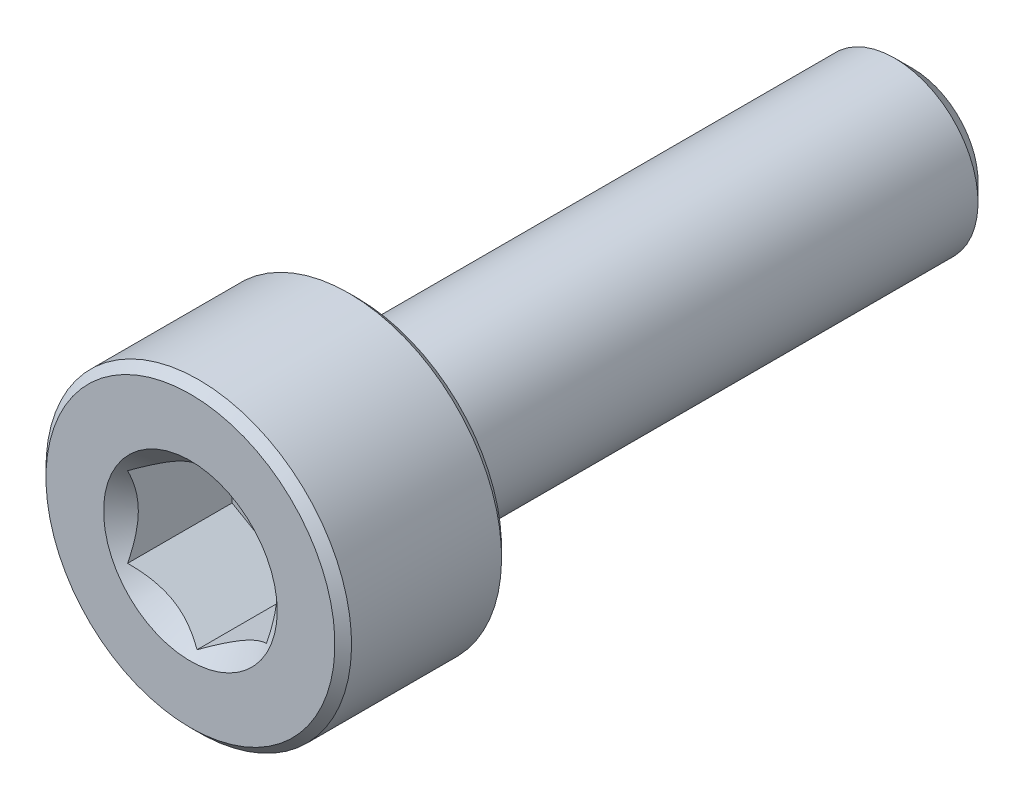
SolidWorks part; units mm, degrees
ref_plane "Front Plane" through (0, 0, 0) normal (0, 0, 1) x (1, 0, 0)
ref_plane "Top Plane" through (0, 0, 0) normal (0, 1, 0) x (1, 0, 0)
ref_plane "Right Plane" through (0, 0, 0) normal (1, 0, 0) x (0, 0, -1)
sketch "Sketch1" plane through (0, 0, 0) normal (1, 0, 0) x (0, 0, -1)
  line L0 (-6.5, 0) -> (6.5, 0) construction
  line L1 (6.5, 0) -> (6.5, 1.1752) construction
  line L2 (6.5, 1.1752) -> (6.1752, 1.5) construction
  line L3 (6.1752, 1.5) -> (6.125, 1.5) construction
  line L4 (6.125, 1.5) -> (-3.5, 1.5) construction
  line L5 (-3.5, 1.5) -> (-3.5, 2.75) construction
  line L6 (-3.5, 2.75) -> (-6.5, 2.75) construction
  line L7 (-6.5, 2.75) -> (-6.5, 0) construction
  line L8 (6.5, 1.1752) -> (6.5, 1.5) construction
  line L9 (6.4688, 1.5541) -> (6.7188, 1.1211) construction
  line L10 (6.7188, 1.1211) -> (6.9688, 1.5541) construction
  line L11 (6.9688, 1.5541) -> (6.4688, 1.5541) construction
  line L12 (6.7188, 1.5541) -> (6.7188, 1.5) construction
  line L13 (6.7188, 1.1211) -> (6.7188, 1.1752) construction
  line L14 (6.6875, 1.1752) -> (6.75, 1.1752) construction
  line L15 (6.5, 1.5) -> (6.9375, 1.5) construction
  line L16 (6.4844, 1.5271) -> (6.9531, 1.5271) construction
  line L17 (6.5, 0) -> (6.5, -1.5) construction
  line L18 (-3.65, 2.75) -> (-3.5, 2.6) construction
  line L19 (-6.35, 2.75) -> (-6.5, 2.6) construction
  line L20 (-3.5, 1.5) -> (-3.5, 0) construction
  line L21 (-3.5, 0.75) -> (-0.1667, 0.75) construction
  line L22 (-0.1667, 0.75) -> (3.1667, 0.75) construction
  line L23 (3.1667, 0.75) -> (6.5, 0.75) construction
  line L24 (-0.1667, 0.75) -> (-0.1667, 1.5) construction
  line L25 (-0.1667, 1.5) -> (-0.1667, 2.75) construction
  line L26 (3.1667, 0.75) -> (3.1667, 2.75) construction
  point P0 (-6.5, 1.25)
  point P3 (5.25, 1.5)
  point P4 (0, 0)
  point P18 (3.1667, 1.5)
  point P22 (6.7188, 1.1752)
  point P24 (6.125, 1.5)
  point P25 (6.7188, 1.5)
  point P28 (6.7188, 1.5271)
  point P29 (5.25, -1.5)
  point P30 (-0.1667, 1.5)
  point P31 (-5, 2.75)
  point P37 (-4.025, 2.75)
  point P38 (-6.275, 2.75)
  point P45 (-0.1667, 0.75)
  point P46 (3.1667, 0.75)
  dimension "D2" = 0.0625
  dimension "D7" = 0.15
  dimension "D8" = 0.15
  dimension "D9" = 0.15
  dimension "D10" = 0.075
  dimension "D11" = 0.375
  dimension "Drive Size" = 2.5
  dimension "Head Diameter" = 5.5
  dimension "Head Height" = 3
  dimension "Thread Pitch" = 0.5
  dimension "Thread Size" = 3
  dimension "Length" = 10
  dimension "D12" = 0.375
  dimension "D4" = 1.25
  dimension "D3" = 45
sketch "Sketch2" plane through (0, 0, 0) normal (1, 0, 0) x (0, 0, -1)
  line L0 (-6.5, 0) -> (-6.5, 2.6)
  line L1 (-6.35, 2.75) -> (-3.65, 2.75)
  line L2 (-3.5, 2.6) -> (-3.5, 1.65)
  line L4 (6.1752, 1.5) -> (6.5, 1.1752)
  line L5 (6.5, 1.1752) -> (6.5, 0)
  line L6 (-3.5, 2.75) -> (-6.5, 2.75) construction
  line L7 (6.5, 0) -> (-6.5, 0)
  line L8 (-6.35, 2.75) -> (-6.5, 2.6) construction
  line L10 (-6.35, 2.75) -> (-6.5, 2.6)
  line L14 (-3.65, 2.75) -> (-3.5, 2.6) construction
  line L16 (-3.65, 2.75) -> (-3.5, 2.6)
  line L17 (-3.5, 1.5) -> (-3.5, 2.75) construction
  line L19 (-3.35, 1.5) -> (6.1752, 1.5)
  line L20 (6.125, 1.5) -> (-3.5, 1.5) construction
  arc A1 (-3.5, 1.65) -> (-3.35, 1.5) centre (-3.35, 1.65) ccw
  dimension "D3" = 0.15
revolve "Revolve1" add sketch "Sketch2" angle 360 about L7
sketch "Sketch3" plane through (0, 0, 6.5) normal (0, 0, 1) x (1, 0, 0)
  line L1 (1.25, -0.7217) -> (1.25, 0.7217)
  line L2 (1.25, 0.7217) -> (0, 1.4434)
  line L3 (0, 1.4434) -> (-1.25, 0.7217)
  line L4 (-1.25, 0.7217) -> (-1.25, -0.7217)
  line L5 (-1.25, -0.7217) -> (0, -1.4434)
  line L6 (0, -1.4434) -> (1.25, -0.7217)
  circle A0 centre (0, 0) radius 1.25 construction
  circle A1 centre (0, 0) radius 2.75 construction
  circle A2 centre (0, 0) radius 2.75 construction
  circle A3 centre (0, 0) radius 1.4434 construction
  point P13 (0, 0)
extrude "Cut-Extrude1" cut sketch "Sketch3" against normal offset from surface (2 mm away) 1 up to face at (0, 2.6, 3.5)
sketch "Sketch4" plane through (0, 0, 6.5) normal (0, 0, 1) x (1, 0, 0)
  circle A0 centre (0, 0) radius 1.5625
  dimension "D1" = 3.125
extrude "Cut-Extrude2" cut sketch "Sketch4" against normal up to vertex (1.5 mm away) draft 45 up to point (0, 2.75, 5)
sketch "Sketch11" plane through (0, 0, 0) normal (1, 0, 0) x (0, 0, -1)
  line L0 (-6.5, 0) -> (6.5, 0) construction
  line L1 (-6.5, 0) -> (6.5, 0) construction
  line L2 (-1.625, 0) -> (-1.625, 1.5) construction
  line L3 (6.125, 1.5) -> (-3.5, 1.5) construction
  line L4 (4.625, 0) -> (4.625, 1.5) construction
  line L6 (6.5, 1.1752) -> (6.5, 1.5) construction
  point P2 (-1.625, 0)
  point P3 (4.625, 0)
  dimension "D1" = 1.875
  dimension "D2" = 1.875
equation "\"D2@Sketch1\" = \"Thread Pitch@Sketch1\" / 8"
equation "\"D7@Sketch1\" = \"Head Height@Sketch1\" * .05"
equation "\"D8@Sketch1\"=\"D7@Sketch1\""
equation "\"D9@Sketch1\"=\"D7@Sketch1\""
equation "\"D10@Sketch1\"=\"D7@Sketch1\"/2"
equation "\"D11@Sketch1\"=\"D10@Sketch1\"*5"
equation "\"D4@Sketch1\"=\"Thread Pitch@Sketch1\"*2.5"
equation "\"D12@Sketch1\"=\"Thread Pitch@Sketch1\"*.75"
equation "\"D3@Sketch2\" = \"Thread Size@Sketch1\" * 0.05"
equation "\"D1@Sketch11\"=\"Length@Sketch1\"*0.1875"
equation "\"D2@Sketch11\"=\"D1@Sketch11\""
equation "\"D1@Sketch4\"= \"Drive Size@Sketch1\" * 1.25"
equation "\"D4@Helix/Spiral1\" = \"Thread Pitch@Sketch1\""
equation "\"D3@Helix/Spiral1\"=\"Length@Sketch1\"+\"Thread Pitch@Sketch1\""
equation "\"D2@Sketch12\"=\"Head Diameter@Sketch1\"*.0125"
equation "\"D1@Cut-Extrude3\"=\"Head Height@Sketch1\"*.8"
equation "\"D1@CirPattern1\"=\"D3@CirPattern1\"/(1.25*\"D1@Sketch12\")"
